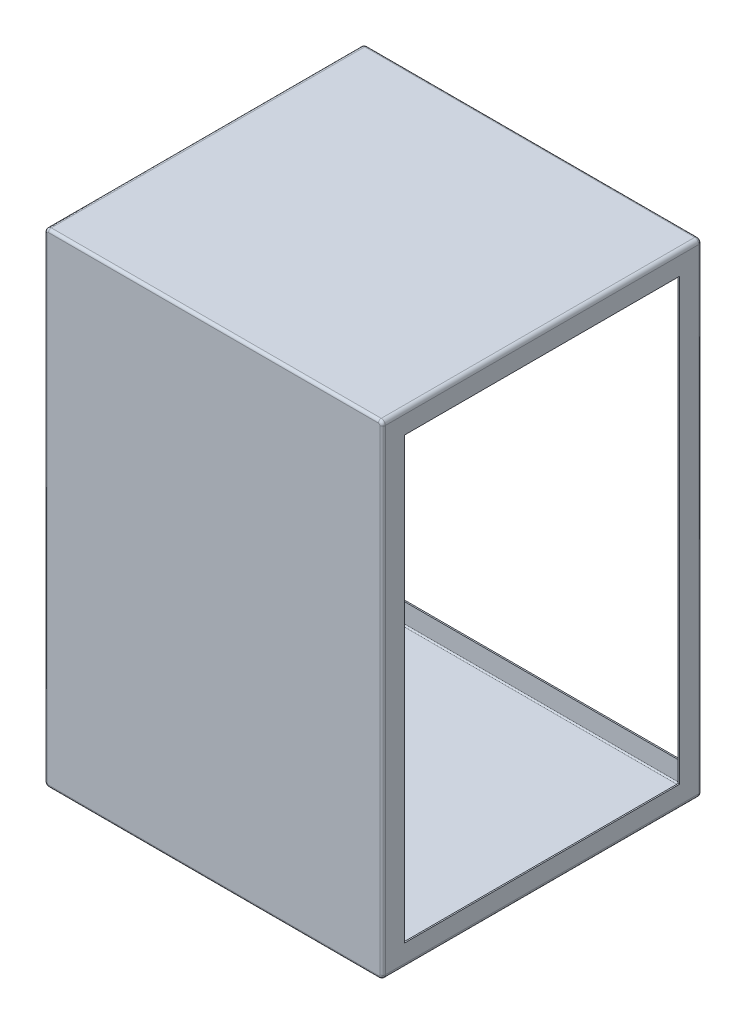
SolidWorks part; units mm, degrees
ref_plane "Спереди" through (0, 0, 0) normal (0, 0, 1) x (1, 0, 0)
ref_plane "Сверху" through (0, 0, 0) normal (0, 1, 0) x (1, 0, 0)
ref_plane "Справа" through (0, 0, 0) normal (1, 0, 0) x (0, 0, -1)
sketch "Эскиз1" plane through (0, 0, 0) normal (0, 0, 1) x (1, 0, 0)
  line L0 (-33.8044, 0) -> (37.3961, 0) construction
  line L1 (0, -31.1634) -> (0, 34.1213) construction
  line L3 (-120, -175) -> (120, -175)
  line L4 (-122, -173) -> (-122, 173)
  line L5 (-120, 175) -> (120, 175)
  line L6 (122, -173) -> (122, 173)
  arc A0 (-122, 173) -> (-120, 175) centre (-120, 173) cw
  arc A1 (120, 175) -> (122, 173) centre (120, 173) cw
  arc A2 (-120, -175) -> (-122, -173) centre (-120, -173) cw
  arc A3 (120, -175) -> (122, -173) centre (120, -173) ccw
  point P11 (-122, 175)
  point P14 (122, 175)
  point P17 (-122, -175)
  dimension "D3" = 2
  dimension "D1" = 350
  dimension "D2" = 244
extrude "Вытянуть-Тонкостенный1" add sketch "Эскиз1" along normal blind 232 thin
sketch "Эскиз2" plane through (123, 0, 0) normal (1, 0, 0) x (0, 0, -1)
  line L0 (0, 0) -> (-300.9003, 0) construction
  line L1 (-216, -160) -> (-16, -160)
  line L2 (-216, -160) -> (-216, 160)
  line L3 (-216, 160) -> (-16, 160)
  line L4 (-16, -160) -> (-16, 160)
  line L5 (-116, 208.5566) -> (-116, -206.9252) construction
  line L6 (-232, -173) -> (-232, 173) construction
  line L7 (0, -173) -> (0, 173) construction
  dimension "D1" = 200
  dimension "D2" = 320
extrude "Вырез-Вытянуть1" cut sketch "Эскиз2" against normal blind 500
sketch "Эскиз3" plane through (0, 0, 232) normal (0, 0, 1) x (1, 0, 0)
  line L4 (-123, 173) -> (-123, -173)
  line L5 (-120, -176) -> (120, -176)
  line L6 (123, -173) -> (123, 173)
  line L7 (120, 176) -> (-120, 176)
  line L8 (-123, 173) -> (-123, -173)
  line L9 (-120, -176) -> (120, -176)
  line L10 (123, -173) -> (123, 173)
  line L11 (120, 176) -> (-120, 176)
  arc A4 (-120, 176) -> (-123, 173) centre (-120, 173) ccw
  arc A5 (-123, -173) -> (-120, -176) centre (-120, -173) ccw
  arc A6 (120, -176) -> (123, -173) centre (120, -173) ccw
  arc A7 (123, 173) -> (120, 176) centre (120, 173) ccw
  arc A8 (-120, 176) -> (-123, 173) centre (-120, 173) ccw
  arc A9 (-123, -173) -> (-120, -176) centre (-120, -173) ccw
  arc A10 (120, -176) -> (123, -173) centre (120, -173) ccw
  arc A11 (123, 173) -> (120, 176) centre (120, 173) ccw
  dimension "D1" = 0
extrude "Вытянуть1" add sketch "Эскиз3" against normal blind 1
sketch "Эскиз4" plane through (0, 0, 0) normal (0, 0, -1) x (-1, 0, 0)
  line L0 (-82.1175, 0) -> (66.3466, 0) construction
  line L1 (0, 0) -> (0, 114.475) construction
  line L3 (-107, -160) -> (107, -160)
  line L4 (120, 176) -> (-120, 176)
  line L5 (-123, 173) -> (-123, -173)
  line L6 (-120, -176) -> (120, -176)
  line L7 (123, -173) -> (123, 173)
  line L8 (120, 176) -> (-120, 176)
  line L9 (-123, 173) -> (-123, -173)
  line L10 (-120, -176) -> (120, -176)
  line L11 (123, -173) -> (123, 173)
  line L12 (-107, -160) -> (-107, 160)
  line L13 (-107, 160) -> (107, 160)
  line L14 (107, -160) -> (107, 160)
  arc A4 (123, 173) -> (120, 176) centre (120, 173) ccw
  arc A5 (-120, 176) -> (-123, 173) centre (-120, 173) ccw
  arc A6 (-123, -173) -> (-120, -176) centre (-120, -173) ccw
  arc A7 (120, -176) -> (123, -173) centre (120, -173) ccw
  arc A8 (123, 173) -> (120, 176) centre (120, 173) ccw
  arc A9 (-120, 176) -> (-123, 173) centre (-120, 173) ccw
  arc A10 (-123, -173) -> (-120, -176) centre (-120, -173) ccw
  arc A11 (120, -176) -> (123, -173) centre (120, -173) ccw
  dimension "D2" = 214
  dimension "D3" = 320
  dimension "D1" = 0
extrude "Вытянуть2" add sketch "Эскиз4" against normal blind 1
fillet "Скругление1" radius 1 16 edges at (121.4142, 174.4142, 231) (122, 0, 231) (121.4142, -174.4142, 231) (0, -175, 231) (-121.4142, -174.4142, 231) (-122, 0, 231) (-121.4142, 174.4142, 231) (-121.4142, 174.4142, 1) (-122, 0, 1) (-121.4142, -174.4142, 1) (0, -175, 1) (121.4142, -174.4142, 1) (122, 0, 1) (121.4142, 174.4142, 1) (0, 175, 231) (0, 175, 1)
fillet "Скругление2" radius 2 16 edges at (-122.1213, 175.1213, 232) (0, 176, 232) (122.1213, 175.1213, 232) (123, 0, 232) (122.1213, -175.1213, 232) (0, -176, 232) (-122.1213, -175.1213, 232) (-122.1213, 175.1213, 0) (0, 176, 0) (122.1213, 175.1213, 0) (123, 0, 0) (122.1213, -175.1213, 0) (0, -176, 0) (-122.1213, -175.1213, 0) (-123, 0, 232) (-123, 0, 0)
